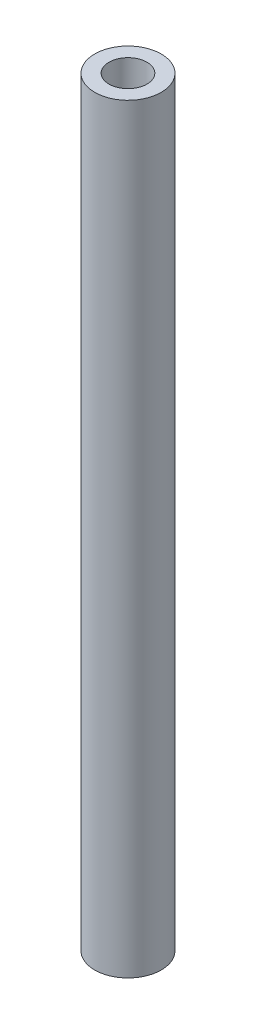
SolidWorks part; units mm, degrees
ref_plane "前视基准面" through (0, 0, 0) normal (0, 0, 1) x (1, 0, 0)
ref_plane "上视基准面" through (0, 0, 0) normal (0, 1, 0) x (1, 0, 0)
ref_plane "右视基准面" through (0, 0, 0) normal (1, 0, 0) x (0, 0, -1)
other "Configuration Table"
sketch "草图1" plane through (0, 0, 0) normal (0, 1, 0) x (1, 0, 0)
  circle A0 centre (0, 0) radius 1.75
  circle A1 centre (0, 0) radius 1
  dimension "D1" = 3.5
  dimension "D2" = 2
extrude "凸台-拉伸1" add sketch "草图1" along normal blind 40
